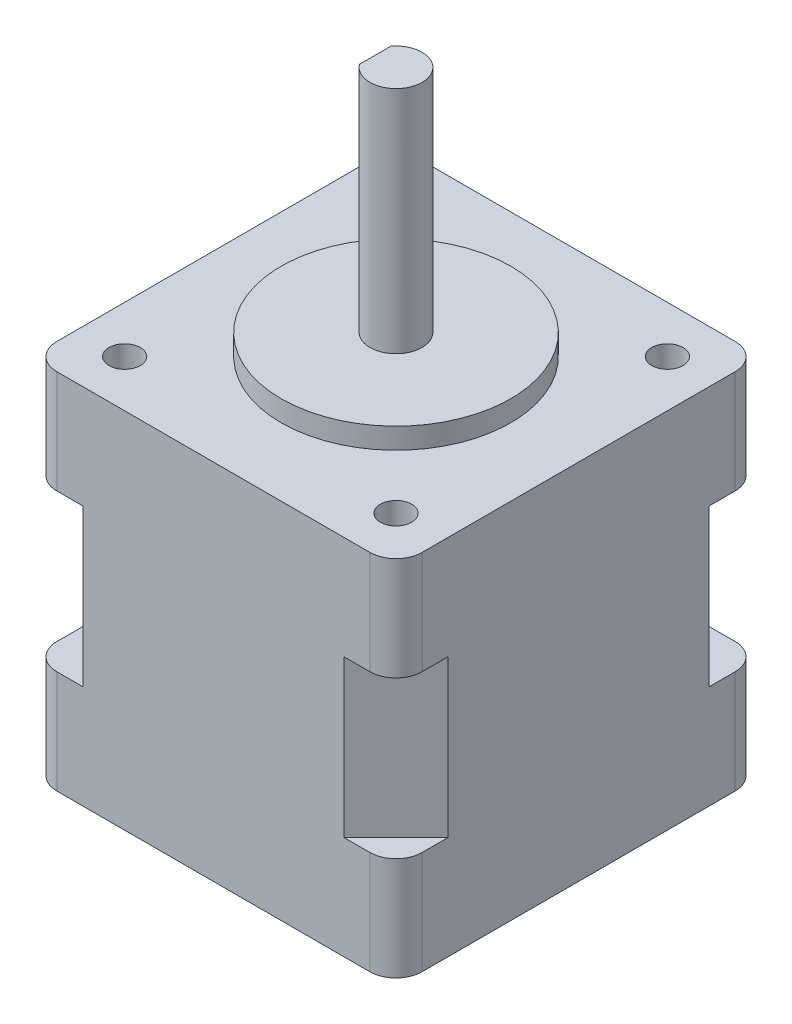
SolidWorks part; units mm, degrees
ref_plane "Plan de face" through (0, 0, 0) normal (0, 0, 1) x (1, 0, 0)
ref_plane "Plan de dessus" through (0, 0, 0) normal (0, 1, 0) x (1, 0, 0)
ref_plane "Plan de droite" through (0, 0, 0) normal (1, 0, 0) x (0, 0, -1)
sketch "Esquisse1" plane through (0, 0, 0) normal (0, 1, 0) x (1, 0, 0)
  line L1 (-17.5, 17.5) -> (17.5, 17.5)
  line L2 (-17.5, 17.5) -> (-17.5, -17.5)
  line L3 (-17.5, -17.5) -> (17.5, -17.5)
  line L4 (17.5, 17.5) -> (17.5, -17.5)
  point P4 (0, 17.5)
  point P6 (-17.5, 0)
  dimension "D1" = 35
extrude "Boss.-Extru.1" add sketch "Esquisse1" along normal blind 34.8
sketch "Esquisse2" plane through (0, 34.8, 0) normal (0, 1, 0) x (1, 0, 0)
  circle A0 centre (0, 0) radius 11
  dimension "D1" = 22
extrude "Boss.-Extru.2" add sketch "Esquisse2" along normal blind 2
sketch "Esquisse3" plane through (0, 36.8, 0) normal (0, 1, 0) x (1, 0, 0)
  circle A2 centre (0, 0) radius 2.5
  dimension "D1" = 5
extrude "Boss.-Extru.3" add sketch "Esquisse3" along normal blind 22
sketch "Esquisse8" plane through (0, 58.8, 0) normal (0, 1, 0) x (1, 0, 0)
  line L0 (2.5, 0) -> (-2, 0) construction
  line L1 (-2, -1.5) -> (-2, 1.5)
  line L2 (-2, -1.5) -> (-3.3893, -1.5)
  line L3 (-3.3893, -1.5) -> (-3.3893, 1.5)
  line L4 (-2, 1.5) -> (-3.3893, 1.5)
  circle A0 centre (0, 0) radius 2.5 construction
  circle A1 centre (0, 0) radius 2.5 construction
  dimension "D1" = 4.5
extrude "Enlèv. mat.-Extru.2" cut sketch "Esquisse8" against normal blind 16.6
ref_plane "Plan1" through (0, 17.4, 0) normal (0, -1, 0) x (-1, 0, 0)
hole_wizard "Diamètre du perçage Ø3.0 (3)1" positions "Esquisse7" profile "Esquisse6" hole size "Ø3.0" standard "DIN"
sketch "Esquisse7" plane through (0, 34.8, 0) normal (0, 1, 0) x (1, 0, 0)
  line L0 (0, 0) -> (0, 4.5387) construction
  line L2 (0, 0) -> (4.1956, 0) construction
  point P0 (-13, 13)
  point P12 (13, 13)
  point P13 (13, -13)
  point P14 (-13, -13)
  dimension "D1" = 26
  dimension "D2" = 26
sketch "Esquisse6" plane through (-13, 34.8, -13) normal (1, 0, 0) x (0, 0, 1)
  line L0 (0, 0) -> (0, 5.1013)
  line L1 (0, 5.1013) -> (1.5, 4.2)
  line L2 (1.5, 4.2) -> (1.5, 0)
  line L5 (1.5, 0) -> (0, 0)
  line L10 (0, 5.1013) -> (-1.5, 4.2) construction
  line L11 (0, -6.35) -> (0, 107.95) construction
  dimension "Diamètre du perçage" = 3
  dimension "Profondeur du perçage" = 4.2
  dimension "Angle de pointe" = 118
fillet "Congé1" radius 2.5 4 edges at (17.5, 17.4, -17.5) (-17.5, 17.4, -17.5) (17.5, 17.4, 17.5) (-17.5, 17.4, 17.5)
sketch "Esquisse4" plane through (0, 17.4, 0) normal (0, 1, 0) x (1, 0, 0)
  line L0 (0, 0) -> (0, 5.1071) construction
  line L1 (0, 0) -> (5.8035, 0) construction
  line L2 (-12.5, 17.5) -> (-17.5, 12.5)
  line L3 (15, 17.5) -> (-15, 17.5) construction
  line L4 (-17.5, 15) -> (-17.5, -15) construction
  line L5 (-17.5, 12.5) -> (-17.5, 17.5)
  line L6 (-17.5, 17.5) -> (-12.5, 17.5)
  line L7 (17.5, 17.5) -> (12.5, 17.5)
  line L8 (17.5, 12.5) -> (17.5, 17.5)
  line L9 (12.5, 17.5) -> (17.5, 12.5)
  line L10 (12.5, -17.5) -> (17.5, -12.5)
  line L11 (17.5, -12.5) -> (17.5, -17.5)
  line L12 (17.5, -17.5) -> (12.5, -17.5)
  line L13 (-17.5, -17.5) -> (-12.5, -17.5)
  line L14 (-17.5, -12.5) -> (-17.5, -17.5)
  line L15 (-12.5, -17.5) -> (-17.5, -12.5)
  dimension "D1" = 5
extrude "Enlèv. mat.-Extru.1" cut sketch "Esquisse4" along normal mid plane 15
sketch "Esquisse5" plane through (-17.5, 0, 0) normal (-1, 0, 0) x (0, 0, 1)
  line L0 (0, 0) -> (0, 2.0466) construction
  line L1 (-15, 0) -> (15, 0) construction
  circle A0 centre (-1, 7) radius 0.7
  circle A1 centre (-1, 5) radius 0.6547
  circle A2 centre (1, 5) radius 0.6547
  circle A3 centre (1, 7) radius 0.7
  dimension "D2" = 1.4
  dimension "D1" = 2
  dimension "D3" = 2
  dimension "D4" = 5
extrude "Boss.-Extru.4" add sketch "Esquisse5" along normal blind 10
equation "\"D3@Esquisse5\"=\"D1@Esquisse5\""
equation "\"D2@Esquisse7\"=\"D1@Esquisse7\""
